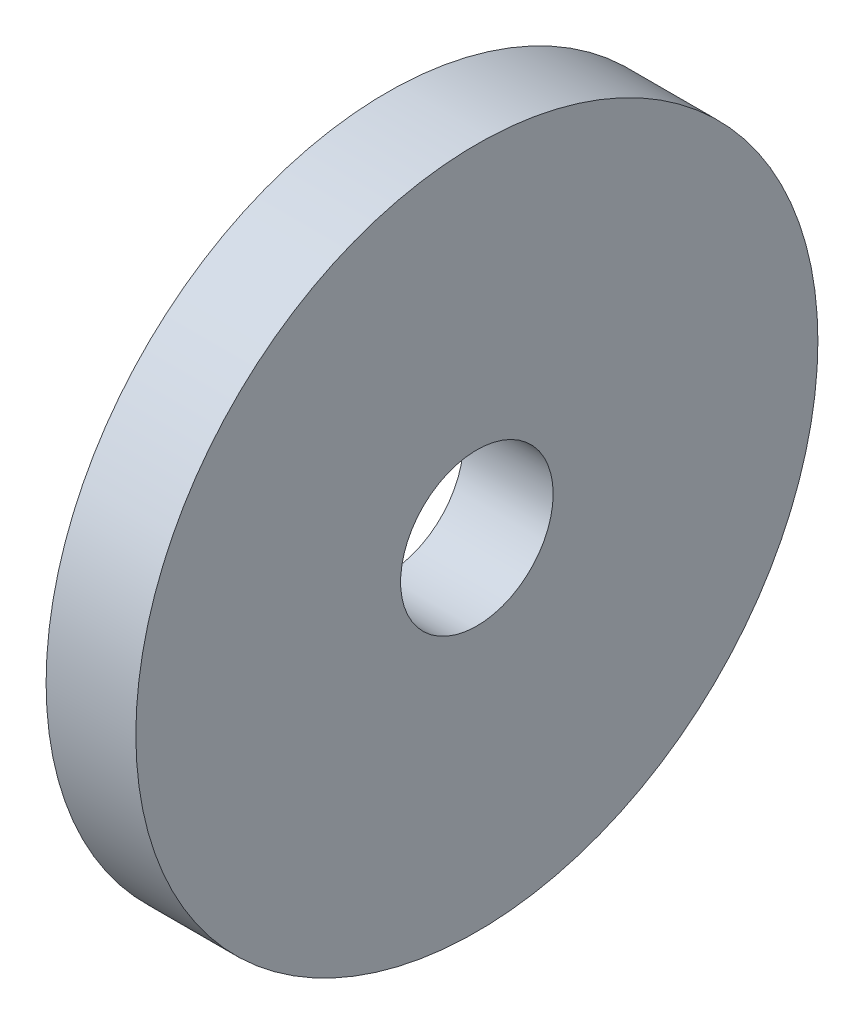
SolidWorks part; units mm, degrees
ref_plane "Front Plane" through (0, 0, 0) normal (0, 0, 1) x (1, 0, 0)
ref_plane "Top Plane" through (0, 0, 0) normal (0, 1, 0) x (1, 0, 0)
ref_plane "Right Plane" through (0, 0, 0) normal (1, 0, 0) x (0, 0, -1)
sketch "Sketch1" plane through (0, 0, 0) normal (1, 0, 0) x (0, 0, -1)
  circle A0 centre (0, 0) radius 19
  circle A1 centre (0, 0) radius 4.25
  dimension "D1" = 8.5
  dimension "D2" = 38
extrude "Boss-Extrude1" add sketch "Sketch1" along normal blind 5
